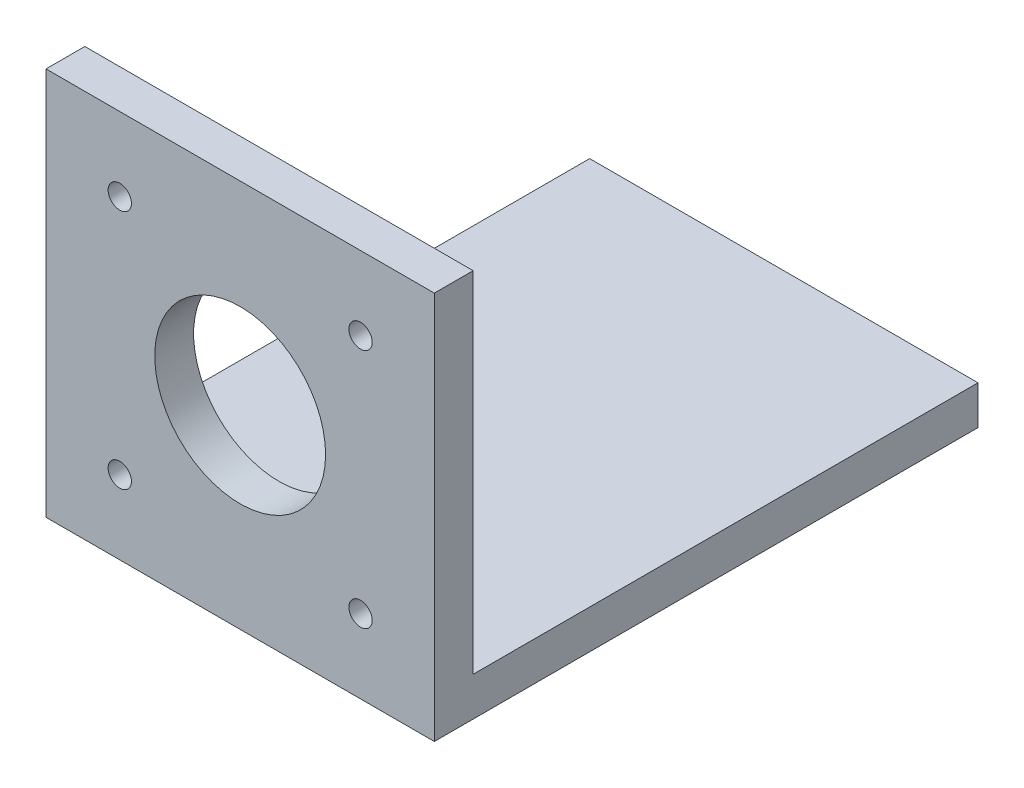
SolidWorks part; units mm, degrees
ref_plane "Front Plane" through (0, 0, 0) normal (0, 0, 1) x (1, 0, 0)
ref_plane "Top Plane" through (0, 0, 0) normal (0, 1, 0) x (1, 0, 0)
ref_plane "Right Plane" through (0, 0, 0) normal (1, 0, 0) x (0, 0, -1)
sketch "Sketch1" plane through (0, 0, 0) normal (1, 0, 0) x (0, 0, -1)
  line L0 (0, 0) -> (0, 50)
  line L1 (0, 0) -> (70, 0)
  line L2 (5, 5) -> (70, 5)
  line L3 (5, 5) -> (5, 50)
  line L4 (70, 0) -> (70, 5)
  line L5 (0, 50) -> (5, 50)
  dimension "D1" = 70
  dimension "D3" = 50
  dimension "D2" = 5
extrude "Boss-Extrude1" add sketch "Sketch1" along normal blind 50
sketch "Sketch3" plane through (0, 0, 0) normal (0, 0, 1) x (1, 0, 0)
  line L0 (25, -1000) -> (25, 49000) construction
  line L1 (50, 0) -> (0, 0) construction
  line L2 (-1000, 25) -> (49000, 25) construction
  line L3 (0, 50) -> (0, 0) construction
  circle A0 centre (25, 25) radius 11
  circle A2 centre (40.5, 40.5) radius 1.5
  circle A3 centre (9.5, 40.5) radius 1.5
  circle A4 centre (9.5, 9.5) radius 1.5
  circle A5 centre (40.5, 9.5) radius 1.5
  point P5 (25, 0)
  point P10 (0, 25)
  dimension "D1" = 22
  dimension "D2" = 15.5
  dimension "D3" = 15.5
  dimension "D4" = 3
extrude "Cut-Extrude1" cut sketch "Sketch3" against normal up to next
